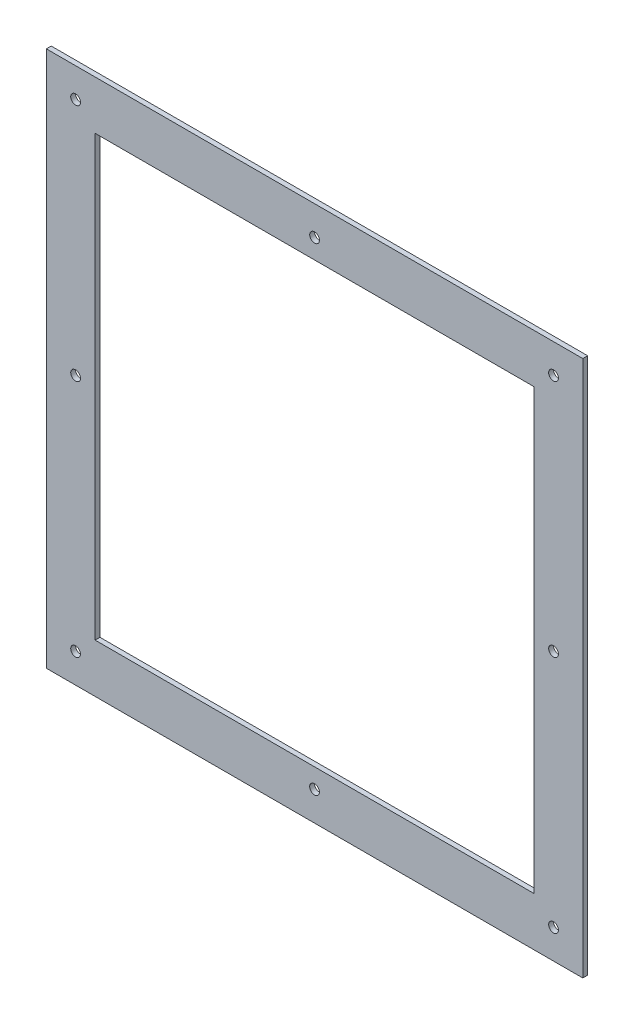
SolidWorks part; units mm, degrees
material "ASTM A36 Steel"
ref_plane "Front Plane" through (0, 0, 0) normal (0, 0, 1) x (1, 0, 0)
ref_plane "Top Plane" through (0, 0, 0) normal (0, 1, 0) x (1, 0, 0)
ref_plane "Right Plane" through (0, 0, 0) normal (1, 0, 0) x (0, 0, -1)
sketch "Sketch1" plane through (0, 0, 0) normal (0, 0, 1) x (1, 0, 0)
  line L1 (-90, -90) -> (90, -90)
  line L2 (-90, -90) -> (-90, 90)
  line L3 (-90, 90) -> (90, 90)
  line L4 (90, -90) -> (90, 90)
  line L5 (-90, -90) -> (90, 90) construction
  line L6 (-90, 90) -> (90, -90) construction
  point P0 (0, 0)
  dimension "D1" = 180
extrude "Extrude-Thin1" add sketch "Sketch1" along normal blind 2 thin
sketch "Sketch2" plane through (0, 0, 2) normal (0, 0, 1) x (1, 0, 0)
  circle A0 centre (0, 98) radius 2
  dimension "D1" = 4
  dimension "D2" = 98
extrude "Cut-Extrude1" cut sketch "Sketch2" against normal blind 10
pattern_linear "LPattern1" count 2 spacing 98 along (1, 0, 0) count 2 spacing 98 along (-1, 0, 0) of "Cut-Extrude1"
pattern_linear "LPattern2" count 3 spacing 98 along (0, -1, 0) of "LPattern1"
pattern_linear "LPattern3" count 3 spacing 196 along (0, -1, 0) of "Cut-Extrude1"
